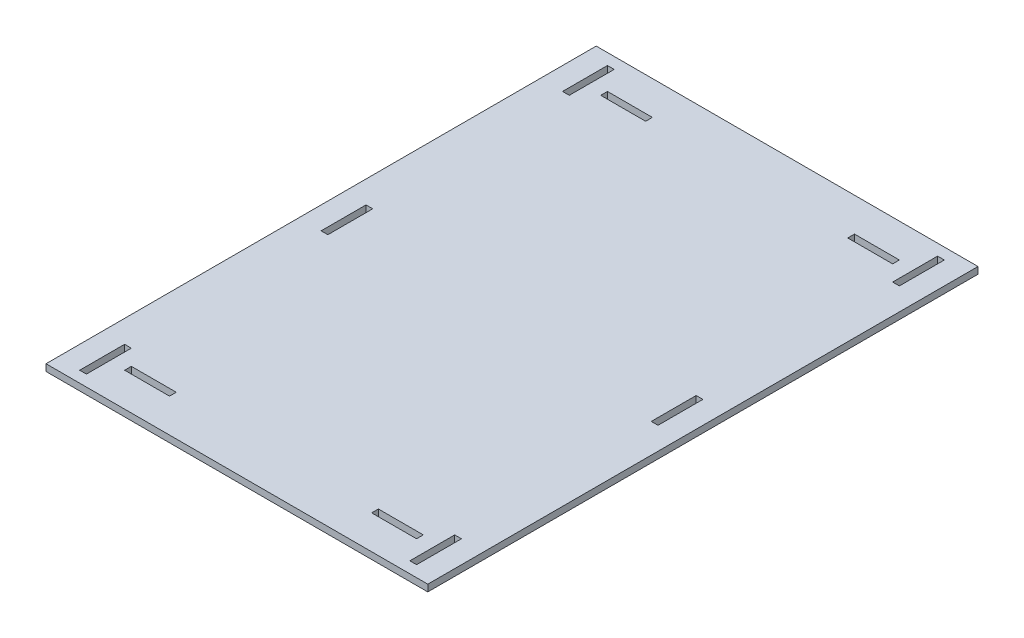
SolidWorks part; units mm, degrees
ref_plane "Front Plane" through (0, 0, 0) normal (0, 0, 1) x (1, 0, 0)
ref_plane "Top Plane" through (0, 0, 0) normal (0, 1, 0) x (1, 0, 0)
ref_plane "Right Plane" through (0, 0, 0) normal (1, 0, 0) x (0, 0, -1)
sketch "Sketch1" plane through (0, 0, 0) normal (0, 1, 0) x (1, 0, 0)
  line L1 (0, 0) -> (340, 0)
  line L2 (0, 0) -> (0, 490)
  line L3 (0, 490) -> (340, 490)
  line L4 (340, 0) -> (340, 490)
  dimension "D1" = 490
  dimension "D2" = 340
extrude "Boss-Extrude1" add sketch "Sketch1" along normal blind 6 contours L2 L3 L4 L1
sketch "Sketch2" plane through (0, 6, 0) normal (0, 1, 0) x (1, 0, 0)
  line L1 (20, 480) -> (26, 480)
  line L2 (20, 480) -> (20, 440)
  line L3 (20, 440) -> (26, 440)
  line L4 (26, 480) -> (26, 440)
  line L5 (0, 0) -> (0, 490) construction
  line L7 (0, 490) -> (340, 490) construction
  dimension "D1" = 40
  dimension "D2" = 6
  dimension "D3" = 20
  dimension "D4" = 10
extrude "Cut-Extrude1" cut sketch "Sketch2" against normal blind 6
pattern_linear "LPattern1" count 2 spacing 294 along (1, 0, 0) count 3 spacing 215 along (0, 0, 1) of "Cut-Extrude1"
sketch "Sketch3" plane through (0, 6, 0) normal (0, 1, 0) x (1, 0, 0)
  line L0 (340, 0) -> (340, 490) construction
  line L1 (300, 460) -> (260, 460)
  line L2 (300, 460) -> (300, 454)
  line L3 (300, 454) -> (260, 454)
  line L4 (260, 460) -> (260, 454)
  line L5 (0, 490) -> (340, 490) construction
  dimension "D1" = 40
  dimension "D2" = 6
  dimension "D3" = 40
  dimension "D4" = 30
extrude "Cut-Extrude2" cut sketch "Sketch3" against normal blind 10
pattern_linear "LPattern2" count 2 spacing 220 along (-1, 0, 0) count 2 spacing 424 along (0, 0, 1) of "Cut-Extrude2"
